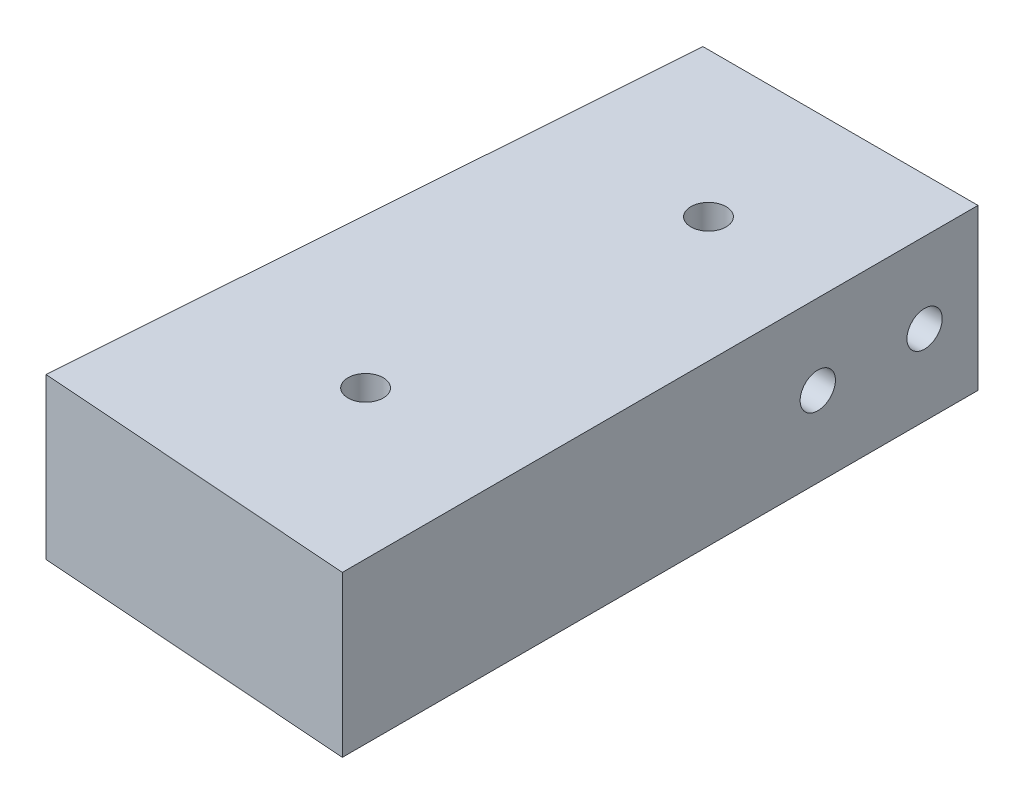
SolidWorks part; units mm, degrees
material "ABS"
ref_plane "前视基准面" through (0, 0, 0) normal (0, 0, 1) x (1, 0, 0)
ref_plane "上视基准面" through (0, 0, 0) normal (0, 1, 0) x (1, 0, 0)
ref_plane "右视基准面" through (0, 0, 0) normal (1, 0, 0) x (0, 0, -1)
other "Configuration Table"
sketch "草图1" plane through (0, 0, 0) normal (0, 1, 0) x (1, 0, 0)
  line L0 (0, -10) -> (-1.0892, -24.9604) construction
  line L1 (0, 0) -> (680, 0) construction
  line L2 (0, 0) -> (0, 15) construction
  line L3 (0, 15) -> (680, 15) construction
  line L4 (680, 0) -> (680, 15) construction
  line L5 (0, -10) -> (680, -59.51) construction
  line L6 (-1.0892, -24.9604) -> (678.9108, -74.4704) construction
  line L7 (680, -59.51) -> (678.9108, -74.4704) construction
  line L8 (0, 0) -> (0, -10) construction
  line L9 (0, -10) -> (19.9472, -11.4523) construction
  line L10 (19.9472, -11.4523) -> (20.781, 0) construction
  line L11 (20.781, 0) -> (0, 0) construction
  line L12 (654.2534, 0) -> (650.0792, -57.3315)
  line L13 (650.0792, -57.3315) -> (680, -59.51)
  line L14 (680, -59.51) -> (680, 0)
  line L15 (680, 0) -> (654.2534, 0)
  line L16 (570.2904, -51.5222) -> (571.6245, -33.1995) construction
  line L17 (570.2904, -51.5222) -> (-45.7125, -51.5222) construction
  dimension "D1" = 15
  dimension "D2" = 15
  dimension "D3" = 680
  dimension "D4" = 20
  dimension "D5" = 80
  dimension "D6" = 681.8
  dimension "D7" = 30
  dimension "D8" = 10
extrude "凸台-拉伸1" add sketch "草图1" along normal blind 15
sketch "草图2" plane through (0, 0, 0) normal (0, -1, 0) x (1, 0, 0)
  circle A0 centre (668.3073, 13.5396) radius 1.45 construction
  circle A1 centre (666.1289, 43.4604) radius 1.45 construction
  circle A2 centre (668.3073, 13.5396) radius 1.45
  circle A3 centre (666.1289, 43.4604) radius 1.45
extrude "切除-拉伸1" cut sketch "草图2" against normal through all
sketch "草图3" plane through (680, 0, 0) normal (1, 0, 0) x (0, 0, -1)
  circle A0 centre (-15, 7.5) radius 1.45 construction
  circle A1 centre (-5, 7.5) radius 1.45 construction
  circle A2 centre (-15, 7.5) radius 1.45
  circle A3 centre (-5, 7.5) radius 1.45
extrude "切除-拉伸2" cut sketch "草图3" against normal through all
sketch "草图4" plane through (0, 15, 0) normal (0, 1, 0) x (1, 0, 0)
  circle A0 centre (668.3073, -13.5396) radius 1.65
  circle A1 centre (666.1289, -43.4604) radius 1.65
  circle A2 centre (668.3073, -13.5396) radius 1.45 construction
  dimension "D1" = 3.3
extrude "切除-拉伸3" cut sketch "草图4" against normal through all
sketch "草图5" plane through (680, 0, 0) normal (1, 0, 0) x (0, 0, -1)
  circle A0 centre (-15, 7.5) radius 1.65
  circle A1 centre (-5, 7.5) radius 1.65
  dimension "D1" = 3.3
extrude "切除-拉伸4" cut sketch "草图5" against normal through all
